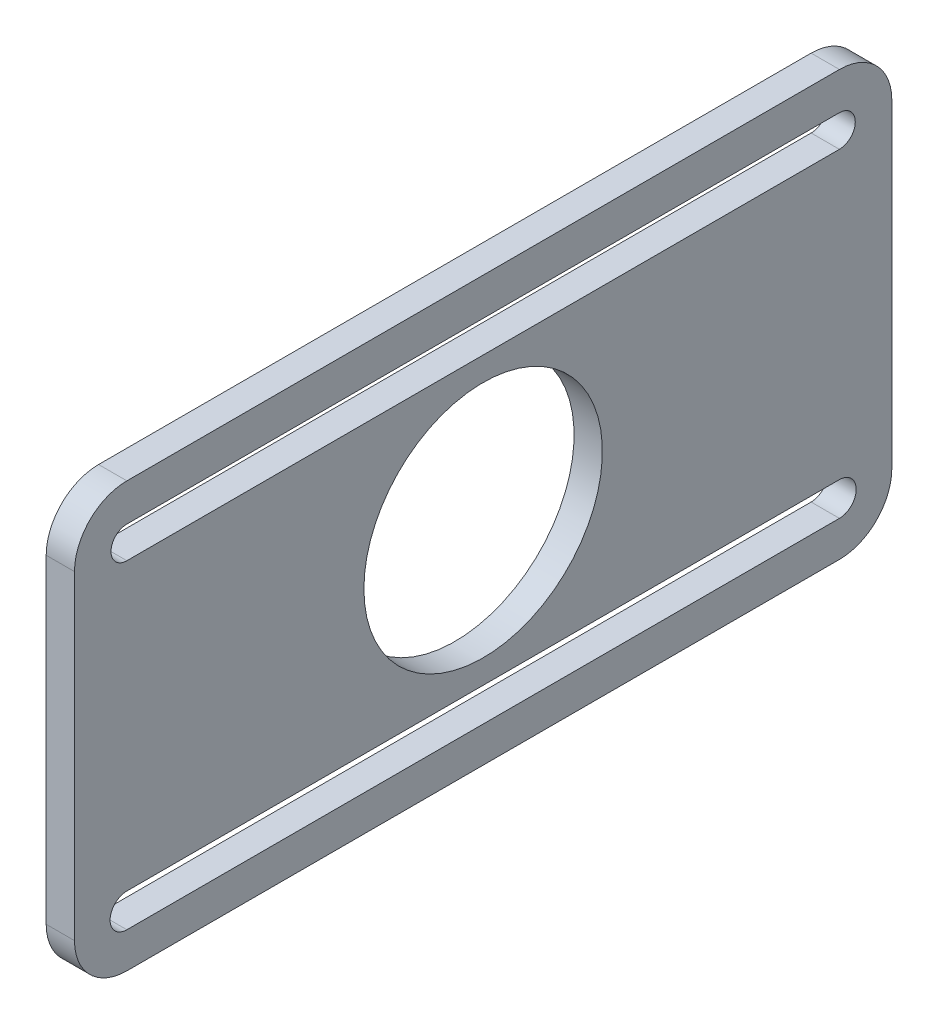
SolidWorks part; units mm, degrees
ref_plane "前视基准面" through (0, 0, 0) normal (0, 0, 1) x (1, 0, 0)
ref_plane "上视基准面" through (0, 0, 0) normal (0, 1, 0) x (1, 0, 0)
ref_plane "右视基准面" through (0, 0, 0) normal (1, 0, 0) x (0, 0, -1)
sketch "草图1" plane through (0, 0, 0) normal (1, 0, 0) x (0, 0, -1)
  line L0 (0, 30.4086) -> (-34, 30.4086) construction
  line L1 (0, -1015.5248) -> (0, -5.0051) construction
  line L8 (-7.4086, -485.2719) -> (-6.9327, -485.2719)
  line L10 (34, 35.4949) -> (-34, 35.4949)
  line L12 (34, -5.0051) -> (-34, -5.0051)
  line L13 (-39, 30.4949) -> (-39, -0.0051)
  line L14 (0, 28.8949) -> (-34, 28.8949)
  line L15 (0, 31.9223) -> (-34, 31.9223)
  line L16 (0, -0.0051) -> (-34, -0.0051) construction
  line L17 (0, -1.6051) -> (-34, -1.6051)
  line L18 (0, 1.5949) -> (-34, 1.5949)
  line L19 (0, 30.4086) -> (34, 30.4086) construction
  line L20 (0, 28.8949) -> (34, 28.8949)
  line L21 (0, 31.9223) -> (34, 31.9223)
  line L22 (-5.123, -0.0051) -> (34, -0.0051) construction
  line L23 (0, -1.6051) -> (34, -1.6051)
  line L24 (0, 1.5949) -> (34, 1.5949)
  line L25 (39, 30.4949) -> (39, -0.0051)
  line L26 (0, 35.4949) -> (0, 1039.0078) construction
  arc A0 (-34, -5.0051) -> (-39, -0.0051) centre (-34, -0.0051) cw
  arc A1 (-34, 35.4949) -> (-39, 30.4949) centre (-34, 30.4949) ccw
  arc A2 (14229.5604, 7457.5626) -> (14229.5737, 7457.4855) centre (14270.7709, 7464.6473) ccw
  circle A4 centre (0, 15.2449) radius 11.3805
  arc A6 (-34, 31.9223) -> (-34, 28.8949) centre (-34, 30.4086) ccw
  arc A8 (-34, 1.5949) -> (-34, -1.6051) centre (-34, -0.0051) ccw
  arc A10 (34, 31.9223) -> (34, 28.8949) centre (34, 30.4086) cw
  arc A12 (34, 1.5949) -> (34, -1.6051) centre (34, -0.0051) cw
  arc A13 (34, 35.4949) -> (39, 30.4949) centre (34, 30.4949) cw
  arc A14 (34, -5.0051) -> (39, -0.0051) centre (34, -0.0051) ccw
  point P20 (-17, 30.4086)
  point P25 (-17, -0.0051)
  point P32 (0, 0)
  point P33 (-17, -2.6996)
  point P34 (0, 0)
  point P35 (-17, 29.5929)
  point P36 (-17, 28.5599)
  point P37 (-17, -0.0051)
  point P38 (-17, 30.4949)
  point P41 (17, 30.4086)
  point P48 (17, -0.0051)
  dimension "D2" = 5
  dimension "D4" = 33.5274
  dimension "D1" = 40.5
extrude "凸台-拉伸1" add sketch "草图1" along normal blind 2.7 contours L12 A14 L25 A13 L10 A1 L13 A0 L24 A12 L23 L17 A8 L18 L21 A10 L20 L14 A6 L15 A4
equation "\"40，5\"=38"
